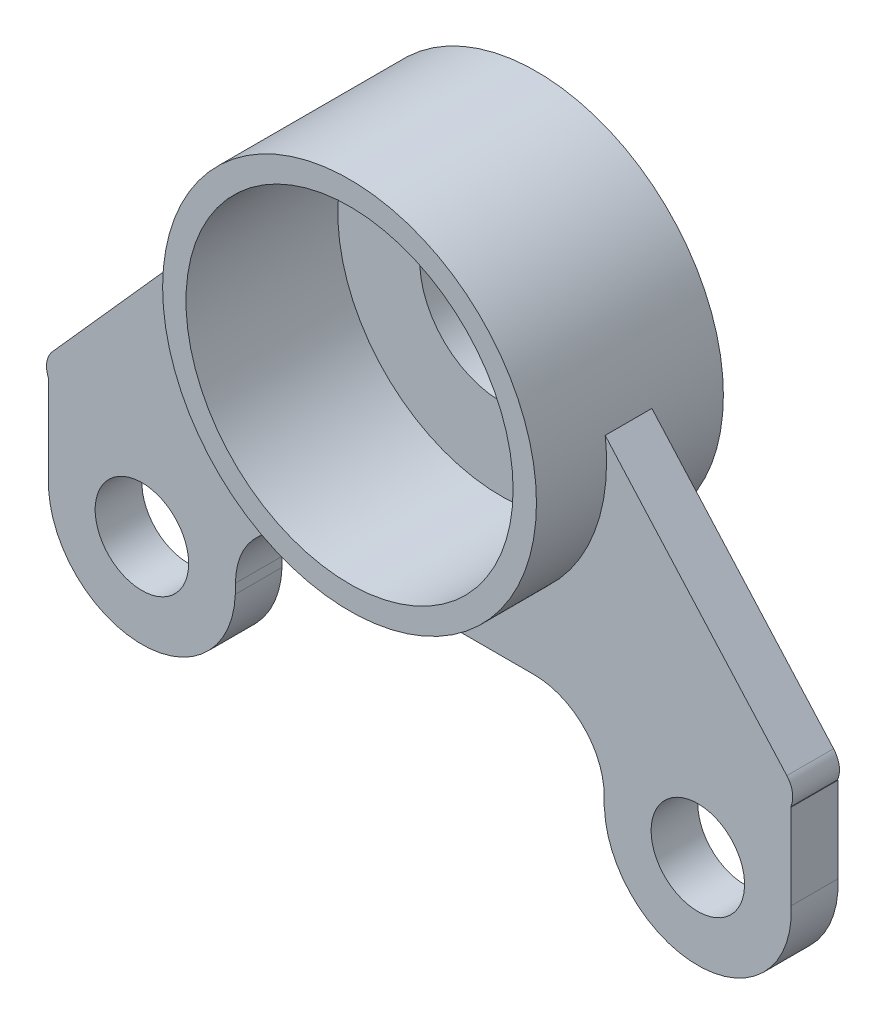
SolidWorks part; units mm, degrees
material "Silicon Rubber"
ref_plane "Front" through (0, 0, 0) normal (0, 0, 1) x (1, 0, 0)
ref_plane "Top" through (0, 0, 0) normal (0, 1, 0) x (1, 0, 0)
ref_plane "Right" through (0, 0, 0) normal (1, 0, 0) x (0, 0, -1)
sketch "Sketch2" plane through (0, 0, 0) normal (0, 0, 1) x (1, 0, 0)
  line L0 (-24.7183, 0) -> (44.0798, 0)
  line L1 (-24.7183, 0) -> (9.6807, 38.594)
  line L2 (9.6807, 38.594) -> (44.0798, 0)
  dimension "D1" = 51.6991
  dimension "D2" = 68.7981
extrude "Boss-Extrude1" add sketch "Sketch2" along normal blind 4
fillet "Fillet1" radius 8 1 edges at (9.6807, 38.594, 2)
fillet "Fillet2" radius 2 2 edges at (-24.7183, 0, 2) (44.0798, 0, 2)
sketch "Sketch3" plane through (0, 0, 0) normal (0, 0, 1) x (1, 0, 0)
  line L0 (-22.0816, 1.1819) -> (-6.0816, 1.1819)
  line L1 (-6.0816, 1.1819) -> (-6.0816, -6.8181)
  line L2 (-6.0816, -6.8181) -> (-22.0816, -6.8181)
  line L3 (-22.0816, -6.8181) -> (-22.0816, 1.1819)
  arc A0 (-21.7496, 3.3307) -> (-20.2566, 0) centre (-20.2566, 2) ccw construction
  dimension "D1" = 16
  dimension "D2" = 8
sketch "Sketch8" plane through (0, 0, 4) normal (0, 0, 1) x (1, 0, 0)
  circle A0 centre (9.6807, 18.8214) radius 16
extrude "Boss-Extrude2" add sketch "Sketch3" along normal blind 4
sketch "Sketch10" plane through (0, 0, 4) normal (0, 0, 1) x (1, 0, 0)
  circle A0 centre (-14.0923, -6.5484) radius 8
extrude "Boss-Extrude3" add sketch "Sketch10" against normal blind 4
fillet "Fillet3" radius 6 1 edges at (-6.0816, 0, 2)
sketch "Sketch11" plane through (0, 0, 4) normal (0, 0, 1) x (1, 0, 0)
  circle A0 centre (-14.0923, -6.5484) radius 4
extrude "Cut-Extrude2" cut sketch "Sketch11" against normal blind 4
ref_plane "Plane1" through (9.7, 0, 0) normal (1, 0, 0) x (0, 0, -1)
mirror "Mirror1" about plane through (9.7, 0, 0) normal (1, 0, 0) of "Fillet3", "Boss-Extrude3", "Boss-Extrude2", "Cut-Extrude2"
extrude "Boss-Extrude4" add sketch "Sketch8" along normal blind 6 and the other way blind 10 contours A0
sketch "Sketch13" plane through (0, 0, 10) normal (0, 0, 1) x (1, 0, 0)
  circle A0 centre (9.6807, 18.8214) radius 14
extrude "Cut-Extrude3" cut sketch "Sketch13" against normal blind 13
sketch "Sketch17" plane through (0, 0, -3) normal (0, 0, 1) x (1, 0, 0)
  circle A0 centre (9.6807, 18.8214) radius 7
extrude "Cut-Extrude4" cut sketch "Sketch17" against normal blind 13
